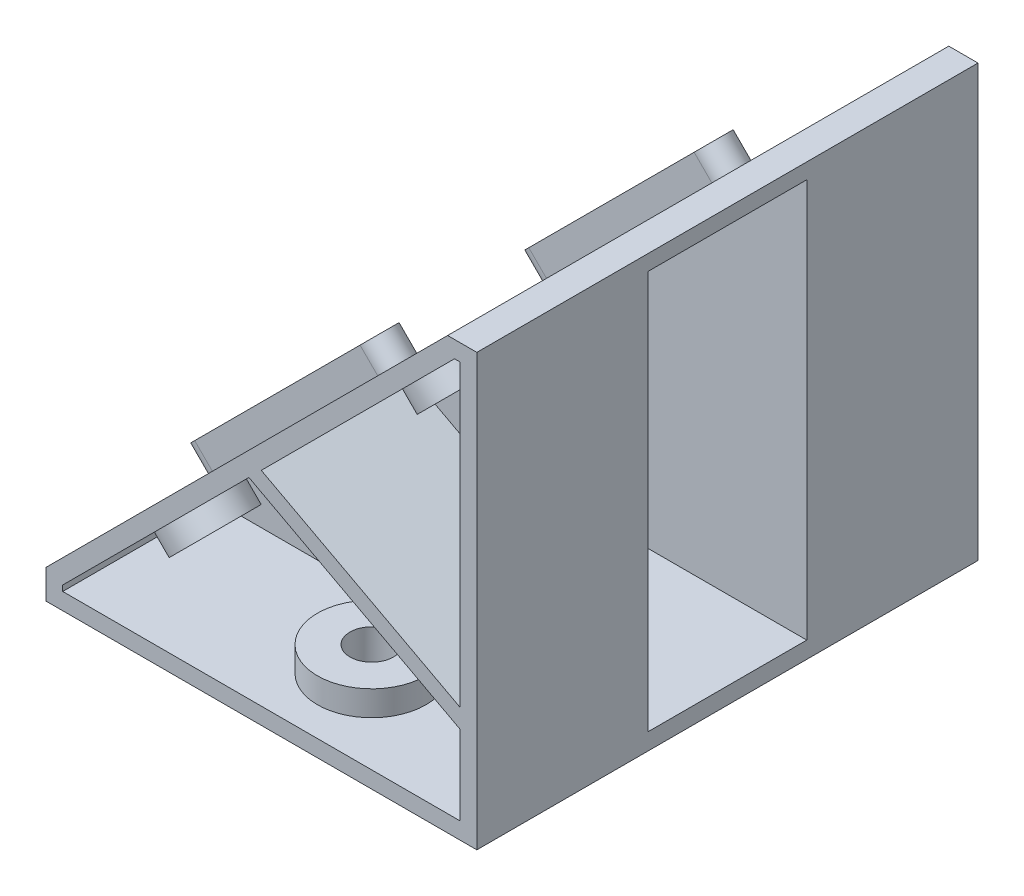
SolidWorks part; units mm, degrees
ref_plane "前视基准面" through (0, 0, 0) normal (0, 0, 1) x (1, 0, 0)
ref_plane "上视基准面" through (0, 0, 0) normal (0, 1, 0) x (1, 0, 0)
ref_plane "右视基准面" through (0, 0, 0) normal (1, 0, 0) x (0, 0, -1)
sketch "草图1" plane through (0, 0, 0) normal (0, 0, 1) x (1, 0, 0)
  line L0 (0, 0) -> (0, 51.5833)
  line L1 (-3.5, 51.5833) -> (-51.5833, 3.5)
  line L2 (-51.5833, 0) -> (0, 0)
  line L3 (-51.5833, 0) -> (-51.5833, 3.5)
  line L4 (0, 51.5833) -> (-3.5, 51.5833)
  dimension "D1" = 68
  dimension "D2" = 45
  dimension "D3" = 3.5
  dimension "D4" = 3.5
extrude "凸台-拉伸1" add sketch "草图1" along normal blind 60
sketch "草图3" plane through (0, 0, 60) normal (0, 0, 1) x (1, 0, 0)
  line L7 (-51.5833, 0) -> (0, 0) construction
  line L8 (-51.5833, 3.5) -> (-51.5833, 0) construction
  line L9 (-3.5, 51.5833) -> (-51.5833, 3.5) construction
  line L10 (0, 51.5833) -> (-3.5, 51.5833) construction
  line L11 (0, 0) -> (0, 51.5833) construction
  line L15 (-49.5833, 2) -> (-2, 2)
  line L16 (-2, 2) -> (-2, 49.5833)
  line L17 (-2, 49.5833) -> (-2.6716, 49.5833)
  line L18 (-2.6716, 49.5833) -> (-49.5833, 2.6716)
  line L19 (-49.5833, 2.6716) -> (-49.5833, 2)
  dimension "D2" = 2
  dimension "D1" = 2
  dimension "D3" = 2
  dimension "D4" = 2
  dimension "D5" = 2
extrude "切除-拉伸1" cut sketch "草图3" against normal blind 18.5
sketch "草图4" plane through (0, 0, 0) normal (0, 0, -1) x (-1, 0, 0)
  line L5 (0, 0) -> (0, 51.5833) construction
  line L6 (0, 51.5833) -> (3.5, 51.5833) construction
  line L7 (3.5, 51.5833) -> (51.5833, 3.5) construction
  line L8 (51.5833, 3.5) -> (51.5833, 0) construction
  line L9 (51.5833, 0) -> (0, 0) construction
  line L15 (2, 2) -> (49.5833, 2)
  line L16 (49.5833, 2) -> (49.5833, 2.6716)
  line L17 (49.5833, 2.6716) -> (2.6716, 49.5833)
  line L18 (2.6716, 49.5833) -> (2, 49.5833)
  line L19 (2, 49.5833) -> (2, 2)
  dimension "D1" = 2
  dimension "D2" = 2
  dimension "D3" = 2
  dimension "D4" = 2
  dimension "D5" = 2
extrude "切除-拉伸2" cut sketch "草图4" against normal blind 18.5
sketch "草图5" plane through (-27.5416, 27.5416, 0) normal (-0.7071, 0.7071, 0) x (0, 0, 1)
  line L0 (30, 34) -> (30, -35.3557) construction
  line L1 (60, 34) -> (0, 34) construction
  line L2 (60, -34) -> (0, -34) construction
  circle A0 centre (10, 18) radius 2.1
  circle A1 centre (10, -24) radius 2.1
  circle A2 centre (50, -24) radius 2.1
  circle A3 centre (50, 18) radius 2.1
  dimension "D1" = 4.2
  dimension "D2" = 4.2
  dimension "D3" = 40
  dimension "D4" = 42
  dimension "D5" = 10
extrude "切除-拉伸3" cut sketch "草图5" against normal blind 3
sketch "草图6" plane through (0, 0, 18.5) normal (0, 0, -1) x (-1, 0, 0)
  line L0 (49.5833, 2) -> (49.5833, 2.6716)
  line L1 (49.5833, 2.6716) -> (2.5251, 49.7297)
  line L2 (49.5833, 2.6716) -> (2.6716, 49.5833) construction
  line L3 (2.5251, 49.7297) -> (-2.7172, 49.7297)
  line L4 (-2.7172, 49.7297) -> (-2.7172, 2)
  line L5 (-2.7172, 2) -> (49.5833, 2)
extrude "切除-拉伸4" cut sketch "草图6" against normal offset from surface (19 mm away) 2 from offset 2 up to face at (-21.1676, 21.1676, 41.5) offset against normal yes
sketch "草图9" plane through (-26.1274, 26.1274, 0) normal (0.7071, -0.7071, 0) x (0, 0, -1)
  line L0 (-30, 36.4749) -> (-30, -36.4749) construction
  line L1 (-60, 36.4749) -> (0, 36.4749) construction
  line L2 (-60, -36.4749) -> (0, -36.4749) construction
  circle A0 centre (-10, 18) radius 2.1
  circle A1 centre (-10, 18) radius 4.5
  circle A2 centre (-10, -24) radius 2.1
  circle A3 centre (-10, -24) radius 4.5
  circle A4 centre (-50, 18) radius 2.1
  circle A5 centre (-50, 18) radius 4.5
  circle A6 centre (-50, -24) radius 2.1
  circle A7 centre (-50, -24) radius 4.5
  dimension "D1" = 9
extrude "凸台-拉伸2" add sketch "草图9" along normal blind 2.5
sketch "草图11" plane through (0, 2, 0) normal (0, 1, 0) x (1, 0, 0)
  line L0 (-49.5833, -18.5) -> (-49.5833, 0) construction
  line L1 (-51.5833, -30) -> (12.2988, -30) construction
  line L2 (-51.5833, -60) -> (-51.5833, 0) construction
  line L3 (-3.5, 0) -> (-51.5833, 0) construction
  circle A0 centre (-22.5833, -10) radius 2.6
  circle A2 centre (-22.5833, -50) radius 2.6
  dimension "D1" = 27
  dimension "D2" = 5.2
  dimension "D3" = 10
extrude "切除-拉伸5" cut sketch "草图11" against normal blind 3
sketch "草图12" plane through (0, 2, 0) normal (0, 1, 0) x (1, 0, 0)
  line L0 (-51.5833, -30) -> (30.1254, -30) construction
  line L1 (-51.5833, -60) -> (-51.5833, 0) construction
  circle A0 centre (-22.5833, -10) radius 2.6
  circle A1 centre (-22.5833, -10) radius 6.5
  circle A2 centre (-22.5833, -50) radius 2.6
  circle A3 centre (-22.5833, -50) radius 6.5
  dimension "D1" = 5.2
  dimension "D2" = 13
extrude "凸台-拉伸3" add sketch "草图12" along normal blind 3
sketch "草图13" plane through (0, 0, 41.5) normal (0, 0, 1) x (1, 0, 0)
  line L0 (-2, 11.5) -> (-27.2879, 24.967)
  line L1 (-2, 2) -> (-2, 49.5833) construction
  line L2 (-2.6716, 49.5833) -> (-49.5833, 2.6716) construction
  line L3 (-27.2879, 24.967) -> (-25.8093, 26.4455)
  line L4 (-25.8093, 26.4455) -> (-2, 13.7659)
  line L5 (-2, 13.7659) -> (-2, 11.5)
  line L6 (-16.0833, 5) -> (-29.0833, 5) construction
  line L7 (-16.0833, 5) -> (-16.0833, 19) construction
  dimension "D1" = 6.5
  dimension "D2" = 2
  dimension "D3" = 14
extrude "凸台-拉伸4" add sketch "草图13" along normal up to surface (18.5 mm away) up to face at (-21.1676, 21.1676, 60)
sketch "草图14" plane through (0, 0, 18.5) normal (0, 0, -1) x (-1, 0, 0)
  line L0 (2, 11.5) -> (2, 13.7659)
  line L1 (2, 13.7659) -> (25.8093, 26.4455)
  line L2 (2, 13.7659) -> (25.8093, 26.4455) construction
  line L3 (25.8093, 26.4455) -> (27.2879, 24.967)
  line L4 (27.2879, 24.967) -> (2, 11.5)
extrude "凸台-拉伸8" add sketch "草图14" along normal up to surface (18.5 mm away) up to face at (-21.1676, 21.1676, 0)
sketch "草图18" plane through (-27.5416, 27.5416, 0) normal (-0.7071, 0.7071, 0) x (0, 0, 1)
  line L0 (10, 18) -> (10, -24) construction
  line L1 (50, 18) -> (50, -24) construction
  line L2 (10, 11) -> (10, -17) construction
  line L3 (12.1, 11) -> (12.1, -17)
  line L4 (7.9, 11) -> (7.9, -17)
  line L5 (50, 11) -> (50, -17) construction
  line L6 (52.1, 11) -> (52.1, -17)
  line L7 (47.9, 11) -> (47.9, -17)
  arc A0 (12.1, 11) -> (7.9, 11) centre (10, 11) ccw
  arc A1 (7.9, -17) -> (12.1, -17) centre (10, -17) ccw
  arc A2 (52.1, 11) -> (47.9, 11) centre (50, 11) ccw
  arc A3 (47.9, -17) -> (52.1, -17) centre (50, -17) ccw
  point P10 (10, -3)
  point P15 (50, -3)
  dimension "D3" = 2.1
  dimension "D4" = 2.1
  dimension "D1" = 28
  dimension "D2" = 28
extrude "凸台-拉伸9" add sketch "草图18" along normal blind 3
